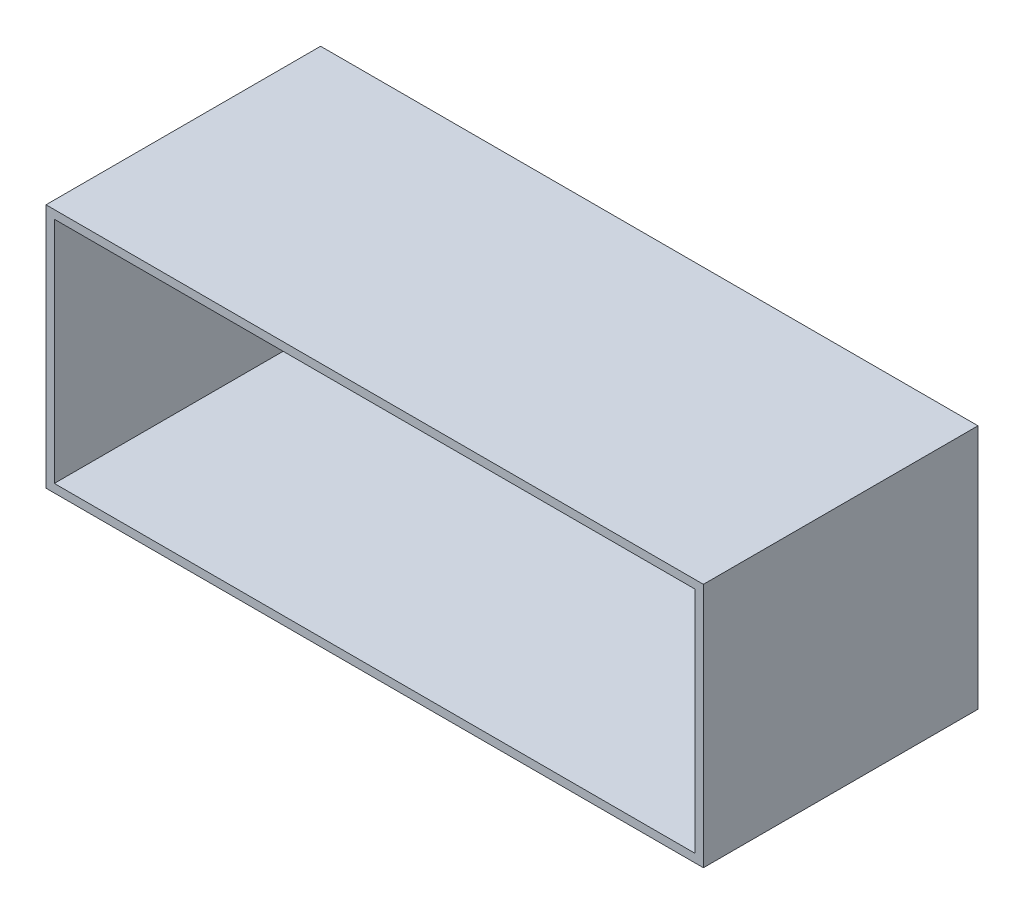
SolidWorks part; units mm, degrees
ref_plane "Front Plane" through (0, 0, 0) normal (0, 0, 1) x (1, 0, 0)
ref_plane "Top Plane" through (0, 0, 0) normal (0, 1, 0) x (1, 0, 0)
ref_plane "Right Plane" through (0, 0, 0) normal (1, 0, 0) x (0, 0, -1)
sketch "Sketch1" plane through (0, 0, 0) normal (0, 0, 1) x (1, 0, 0)
  line L1 (0, 0) -> (158, 0)
  line L2 (0, 0) -> (0, 59)
  line L3 (0, 59) -> (158, 59)
  line L4 (158, 0) -> (158, 59)
  line L5 (2, 2) -> (156, 2)
  line L6 (2, 2) -> (2, 57)
  line L7 (2, 57) -> (156, 57)
  line L8 (156, 2) -> (156, 57)
  dimension "D1" = 2
  dimension "D2" = 156
  dimension "D3" = 158
  dimension "D4" = 2
  dimension "D5" = 57
  dimension "D6" = 59
extrude "Profile" add sketch "Sketch1" along normal blind 66
sketch "Sketch2" plane through (0, 0, 0) normal (0, 0, 1) x (1, 0, 0)
  line L1 (2, 2) -> (156, 2)
  line L2 (2, 2) -> (2, 57)
  line L3 (2, 57) -> (156, 57)
  line L4 (156, 2) -> (156, 57)
extrude "Back" add sketch "Sketch2" along normal blind 2
equation "\"Profile_Depth\"= 66mm"
equation "\"D1@Profile\" = \"Profile_Depth\""
equation "\"Profile_Sketch_1\"= 2mm"
equation "\"D1@Sketch1\" = \"Profile_Sketch_1\""
equation "\"Profile_Sketch_2\"= 156mm"
equation "\"D2@Sketch1\" = \"Profile_Sketch_2\""
equation "\"Profile_Sketch_3\"= 158mm"
equation "\"D3@Sketch1\" = \"Profile_Sketch_3\""
equation "\"Profile_Sketch_4\"= 2mm"
equation "\"D4@Sketch1\" = \"Profile_Sketch_4\""
equation "\"Profile_Sketch_5\"= 57mm"
equation "\"D5@Sketch1\" = \"Profile_Sketch_5\""
equation "\"Profile_Sketch_6\"= 59mm"
equation "\"D6@Sketch1\" = \"Profile_Sketch_6\""
equation "\"Back_Depth\"= 2mm"
equation "\"D1@Back\" = \"Back_Depth\""
equation "\"EnvelopeWidth\"= 158mm"
equation "\"EnvelopeHeight\"= 59mm"
